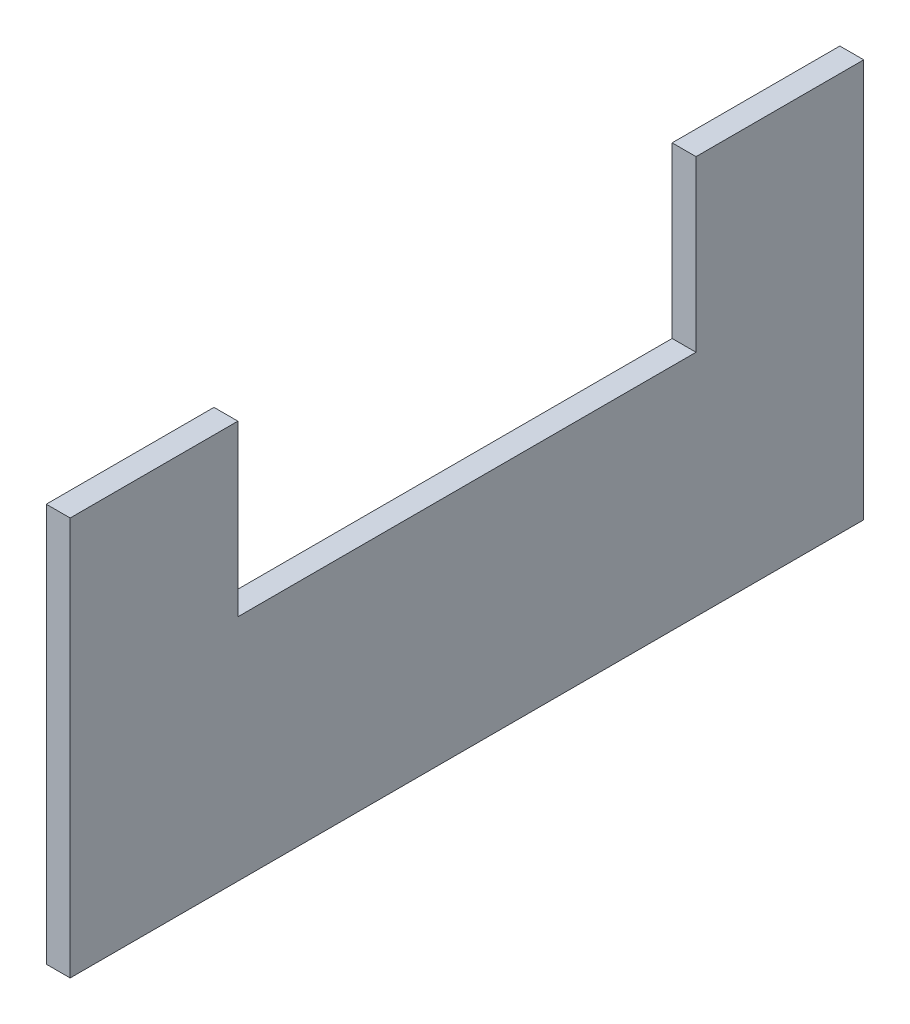
SolidWorks part; units mm, degrees
ref_plane "Front Plane" through (0, 0, 0) normal (0, 0, 1) x (1, 0, 0)
ref_plane "Top Plane" through (0, 0, 0) normal (0, 1, 0) x (1, 0, 0)
ref_plane "Right Plane" through (0, 0, 0) normal (1, 0, 0) x (0, 0, -1)
sketch "Sketch1" plane through (0, 0, 0) normal (1, 0, 0) x (0, 0, -1)
  line L0 (-49.8, 25) -> (-28.75, 25)
  line L2 (-49.8, 25) -> (-49.8, -25)
  line L3 (-49.8, -25) -> (49.8, -25)
  line L4 (49.8, 25) -> (49.8, -25)
  line L5 (0, -25) -> (0, 25) construction
  line L6 (-49.8, 0) -> (49.8, 0) construction
  line L7 (-28.75, 25) -> (-28.75, 3.7369)
  line L8 (-28.75, 3.7369) -> (28.75, 3.7369)
  line L9 (28.75, 3.7369) -> (28.75, 25)
  line L10 (28.75, 25) -> (49.8, 25)
  point P0 (0, 0)
  dimension "D1" = 99.6
  dimension "D2" = 21.05
extrude "Boss-Extrude1" add sketch "Sketch1" along normal blind 3
